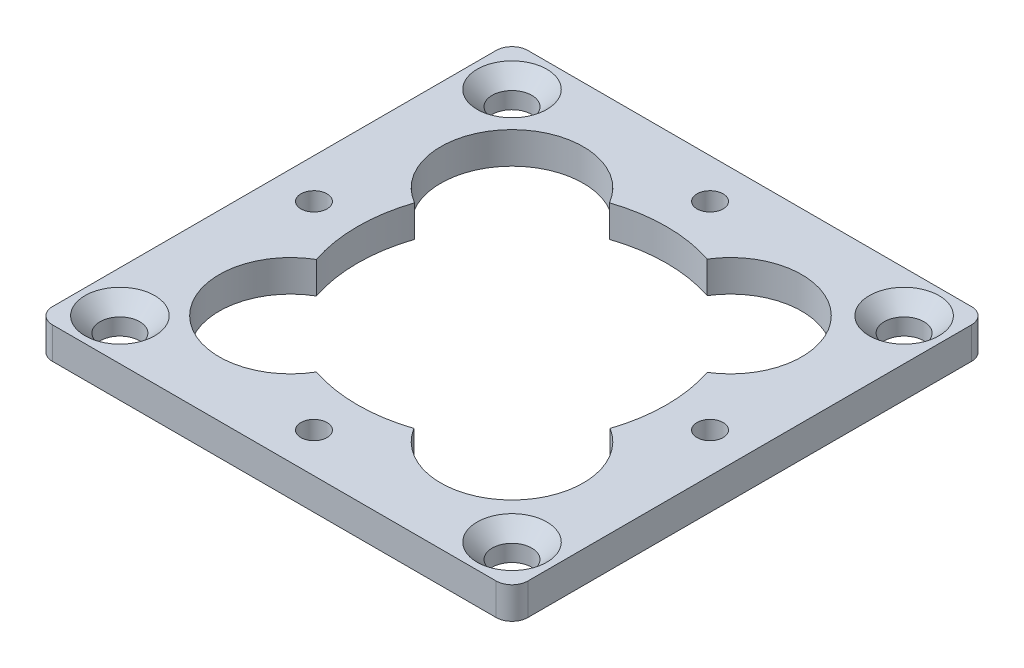
SolidWorks part; units mm, degrees
ref_plane "Спереди" through (0, 0, 0) normal (0, 0, 1) x (1, 0, 0)
ref_plane "Сверху" through (0, 0, 0) normal (0, 1, 0) x (1, 0, 0)
ref_plane "Справа" through (0, 0, 0) normal (1, 0, 0) x (0, 0, -1)
sketch "Эскиз1" plane through (0, 0, 0) normal (0, 1, 0) x (1, 0, 0)
  line L0 (-8.7053, 33.781) -> (-8.7053, -26.219) construction
  line L1 (-38.7053, 33.781) -> (21.2947, 33.781)
  line L2 (-38.7053, 33.781) -> (-38.7053, -26.219)
  line L3 (-38.7053, -26.219) -> (21.2947, -26.219)
  line L4 (21.2947, 33.781) -> (21.2947, -26.219)
  line L5 (-8.7053, -26.219) -> (21.2947, 3.781) construction
  line L6 (21.2947, 3.781) -> (-38.7053, 3.781) construction
  line L7 (16.0434, 28.5298) -> (-8.7053, 3.781) construction
  line L8 (-8.7053, 3.781) -> (-33.454, -20.9677) construction
  line L9 (-33.454, 28.5298) -> (16.0434, -20.9677) construction
  line L11 (-22.6887, 17.7644) -> (5.0833, -10.0075) construction
  line L12 (5.0833, 17.5696) -> (-22.6887, -10.2024) construction
  circle A0 centre (-33.454, 28.5298) radius 2.5
  circle A1 centre (16.0434, 28.5298) radius 2.5
  circle A2 centre (-33.454, -20.9677) radius 2.5
  circle A3 centre (16.0434, -20.9677) radius 2.5
  arc A4 (-27.1957, 9.9742) -> (-27.1957, -2.4122) centre (-8.7053, 3.781) ccw
  circle A5 centre (-33.7053, 3.781) radius 1.65
  circle A6 centre (16.2947, 3.781) radius 1.65
  arc A7 (-14.8985, 22.2714) -> (-27.1957, 9.9742) centre (-22.6887, 17.7644) ccw
  arc A8 (9.8069, 9.9088) -> (-2.5775, 22.2932) centre (5.0833, 17.5696) ccw
  arc A9 (-27.1957, -2.4122) -> (-14.8985, -14.7094) centre (-22.6887, -10.2024) ccw
  arc A10 (-2.5775, -14.7311) -> (9.8069, -2.3468) centre (5.0833, -10.0075) ccw
  arc A11 (-2.5775, 22.2932) -> (-14.8985, 22.2714) centre (-8.7053, 3.781) ccw
  arc A12 (-14.8985, -14.7094) -> (-2.5775, -14.7311) centre (-8.7053, 3.781) ccw
  arc A13 (9.8069, -2.3468) -> (9.8069, 9.9088) centre (-8.7053, 3.781) ccw
  circle A14 centre (-8.7053, 3.781) radius 35 construction
  circle A15 centre (-8.7053, 3.781) radius 25 construction
  circle A16 centre (-8.7053, 28.781) radius 1.65
  circle A17 centre (-8.7053, -21.219) radius 1.65
  dimension "D3" = 45
  dimension "D4" = 45
  dimension "D7" = 45
  dimension "D8" = 3.3
  dimension "D9" = 5
  dimension "D10" = 3.3
  dimension "D11" = 39
  dimension "D12" = 3.3
  dimension "D13" = 3.3
  dimension "D14" = 50
  dimension "D18" = 18
  dimension "D19" = 18
  dimension "D20" = 18
  dimension "D21" = 18
  dimension "D5" = 70
  dimension "D6" = 45
  dimension "D1" = 60
  dimension "D2" = 60
  dimension "D15" = 25
  dimension "D16" = 45
  dimension "D17" = 45
extrude "Бобышка-Вытянуть1" add sketch "Эскиз1" along normal blind 4
fillet "Скругление1" radius 2 4 edges at (-38.7053, 2, -33.781) (21.2947, 2, -33.781) (21.2947, 2, 26.219) (-38.7053, 2, 26.219)
chamfer "Фаска1" distance 1.9 angle 45 4 edges at (16.0434, 4, 23.4677) (16.0434, 4, -26.0298) (-33.454, 4, 23.4677) (-33.454, 4, -26.0298)
